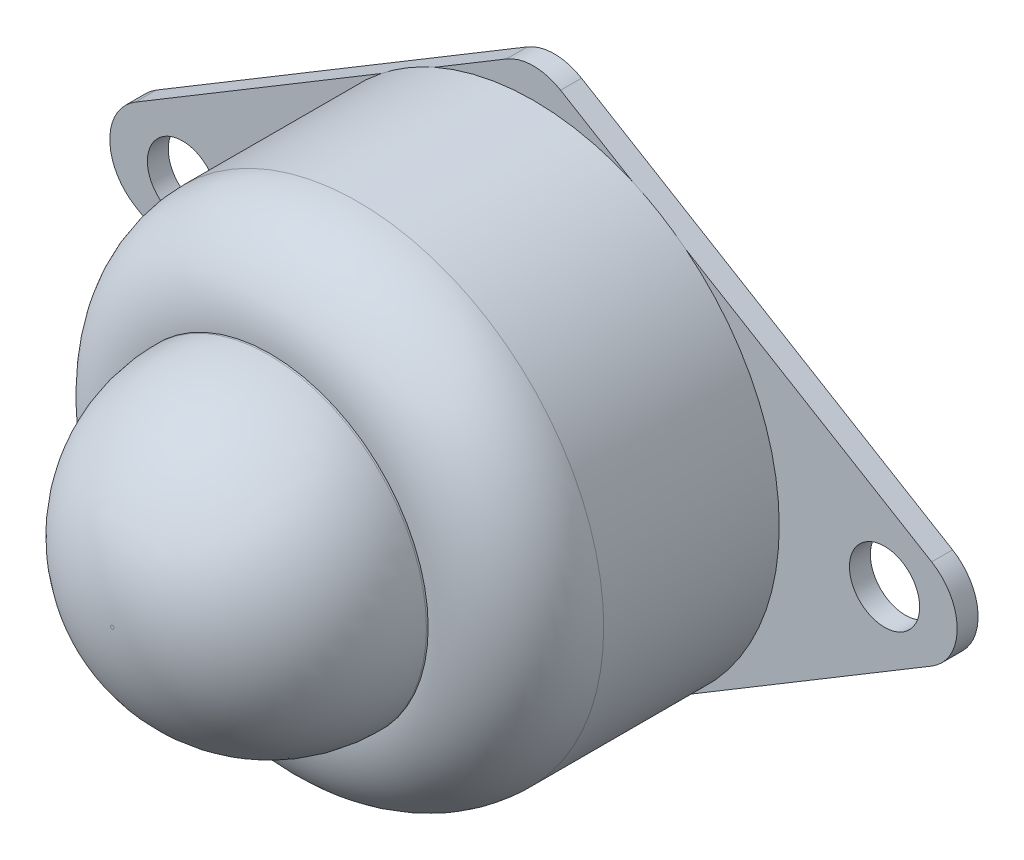
SolidWorks part; units mm, degrees
ref_plane "Plan de face" through (0, 0, 0) normal (0, 0, 1) x (1, 0, 0)
ref_plane "Plan de dessus" through (0, 0, 0) normal (0, 1, 0) x (1, 0, 0)
ref_plane "Plan de droite" through (0, 0, 0) normal (1, 0, 0) x (0, 0, -1)
sketch "Esquisse1" plane through (0, 0, 0) normal (0, 0, 1) x (1, 0, 0)
  line L0 (1.3151, 18.2661) -> (22.4551, 30.9661)
  line L1 (-0.14, 15.6944) -> (48.14, 15.6944) construction
  line L2 (24, 15.6944) -> (24, 31.3944) construction
  line L3 (24, 15.6944) -> (24, -0.0056) construction
  line L5 (25.5449, 30.9661) -> (46.6849, 18.2661)
  line L6 (22.4551, 0.4228) -> (1.3151, 13.1228)
  line L7 (25.5449, 0.4228) -> (46.6849, 13.1228)
  arc A0 (25.5449, 30.9661) -> (22.4551, 30.9661) centre (24, 28.3944) ccw
  arc A1 (46.6849, 13.1228) -> (46.6849, 18.2661) centre (45.14, 15.6944) ccw
  arc A2 (22.4551, 0.4228) -> (25.5449, 0.4228) centre (24, 2.9944) ccw
  arc A3 (1.3151, 13.1228) -> (1.3151, 18.2661) centre (2.86, 15.6944) cw
  circle A4 centre (44, 15.6944) radius 2
  circle A5 centre (4, 15.6944) radius 2
  dimension "D1" = 3
  dimension "D3" = 20
  dimension "D2" = 4.14
  dimension "D4" = 15.7
extrude "Boss.-Extru.1" add sketch "Esquisse1" along normal blind 1.19
sketch "Esquisse2" plane through (0, 0, 1.19) normal (0, 0, 1) x (1, 0, 0)
  line L0 (24, 31.3944) -> (24, -0.0056) construction
  arc A0 (25.5449, 30.9661) -> (22.4551, 30.9661) centre (24, 28.3944) ccw construction
  arc A1 (22.4551, 0.4228) -> (25.5449, 0.4228) centre (24, 2.9944) ccw construction
  circle A2 centre (24, 15.6944) radius 14
extrude "Boss.-Extru.2" add sketch "Esquisse2" along normal blind 15
fillet "Congé1" radius 5 1 edges at (38, 15.6944, 16.19)
sketch "Esquisse3" plane through (0, 0, 16.19) normal (0, 0, 1) x (1, 0, 0)
  circle A0 centre (24, 15.6944) radius 9
extrude "Boss.-Extru.3" add sketch "Esquisse3" along normal blind 9
fillet "Congé2" radius 8.9 1 edges at (33, 15.6944, 25.19)
